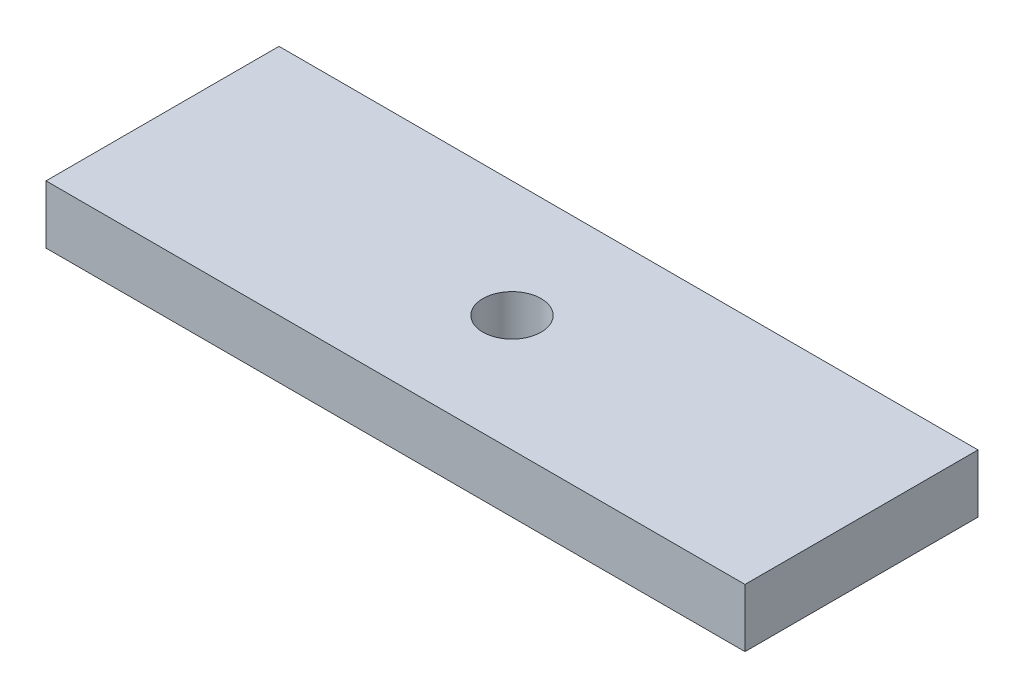
SolidWorks part; units mm, degrees
ref_plane "Front Plane" through (0, 0, 0) normal (0, 0, 1) x (1, 0, 0)
ref_plane "Top Plane" through (0, 0, 0) normal (0, 1, 0) x (1, 0, 0)
ref_plane "Right Plane" through (0, 0, 0) normal (1, 0, 0) x (0, 0, -1)
sketch "Sketch1" plane through (0, 0, 0) normal (0, 1, 0) x (1, 0, 0)
  line L1 (-30, 10) -> (30, 10)
  line L2 (-30, 10) -> (-30, -10)
  line L3 (-30, -10) -> (30, -10)
  line L4 (30, 10) -> (30, -10)
  line L5 (-30, 10) -> (30, -10) construction
  line L6 (-30, -10) -> (30, 10) construction
  point P0 (0, 0)
  dimension "D1" = 60
  dimension "D2" = 20
extrude "Boss-Extrude1" add sketch "Sketch1" along normal blind 5
sketch "Sketch2" plane through (0, 5, 0) normal (0, 1, 0) x (1, 0, 0)
  line L0 (-30, 10) -> (-30, -10) construction
  circle A0 centre (0, 0) radius 2.5
  dimension "D1" = 5
  dimension "D2" = 30
extrude "Cut-Extrude1" cut sketch "Sketch2" against normal through all
